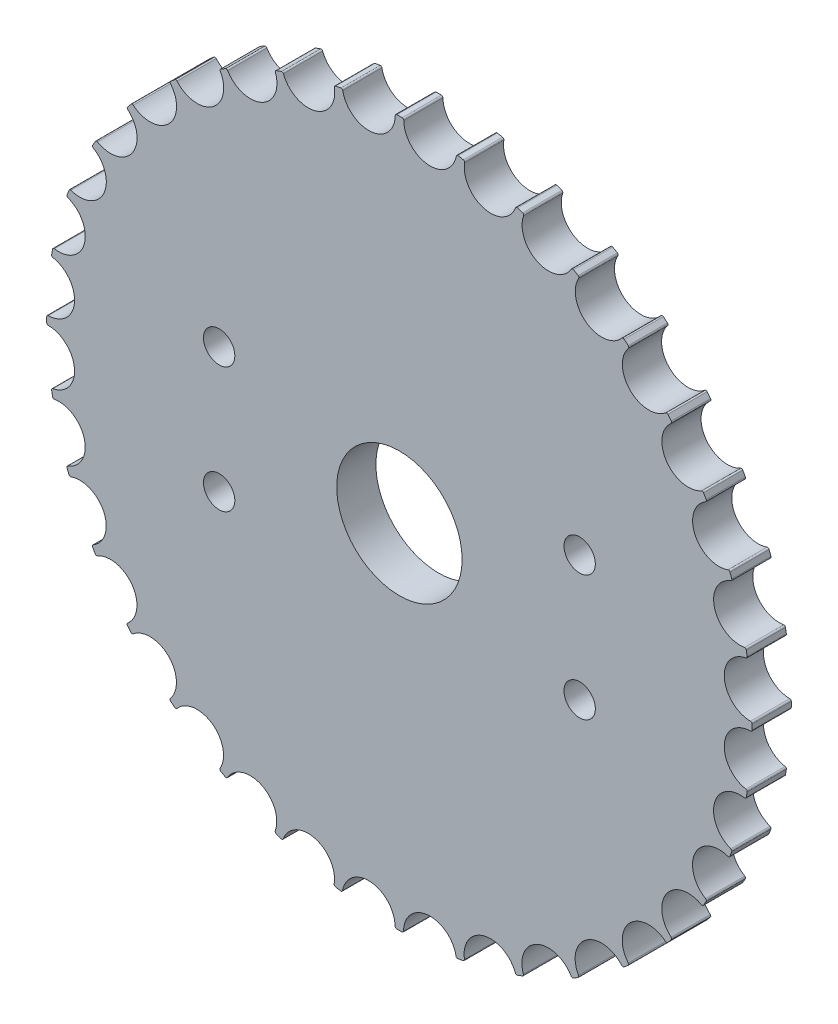
SolidWorks part; units mm, degrees
ref_plane "정면" through (0, 0, 0) normal (0, 0, 1) x (1, 0, 0)
ref_plane "윗면" through (0, 0, 0) normal (0, 1, 0) x (1, 0, 0)
ref_plane "우측면" through (0, 0, 0) normal (1, 0, 0) x (0, 0, -1)
sketch "스케치1" plane through (0, 0, 0) normal (0, 0, 1) x (1, 0, 0)
  circle A0 centre (0, 0) radius 45
extrude "보스-돌출1" add sketch "스케치1" along normal blind 5
sketch "스케치2" plane through (0, 0, 5) normal (0, 0, 1) x (1, 0, 0)
  line L0 (0, 0) -> (0, 53.4651) construction
  line L1 (0, 0) -> (9.1386, 52.0133) construction
  line L2 (0, 0) -> (-9.7027, 52.5525) construction
  circle A0 centre (3.9357, 44.8276) radius 3.38
  circle A2 centre (0, 0) radius 45 construction
  circle A6 centre (11.6601, 43.4631) radius 3.38
  circle A7 centre (19.0303, 40.778) radius 3.38
  circle A8 centre (25.8222, 36.854) radius 3.38
  circle A9 centre (31.8295, 31.8101) radius 3.38
  circle A10 centre (36.8697, 25.7997) radius 3.38
  circle A11 centre (40.7897, 19.0054) radius 3.38
  circle A12 centre (43.4702, 11.6336) radius 3.38
  circle A13 centre (44.83, 3.9083) radius 3.38
  circle A14 centre (44.8276, -3.9357) radius 3.38
  circle A15 centre (43.4631, -11.6601) radius 3.38
  circle A16 centre (40.778, -19.0303) radius 3.38
  circle A17 centre (36.854, -25.8222) radius 3.38
  circle A18 centre (31.8101, -31.8295) radius 3.38
  circle A19 centre (25.7997, -36.8697) radius 3.38
  circle A20 centre (19.0054, -40.7897) radius 3.38
  circle A21 centre (11.6336, -43.4702) radius 3.38
  circle A22 centre (3.9083, -44.83) radius 3.38
  circle A23 centre (-3.9357, -44.8276) radius 3.38
  circle A24 centre (-11.6601, -43.4631) radius 3.38
  circle A25 centre (-19.0303, -40.778) radius 3.38
  circle A26 centre (-25.8222, -36.854) radius 3.38
  circle A27 centre (-31.8295, -31.8101) radius 3.38
  circle A28 centre (-36.8697, -25.7997) radius 3.38
  circle A29 centre (-40.7897, -19.0054) radius 3.38
  circle A30 centre (-43.4702, -11.6336) radius 3.38
  circle A31 centre (-44.83, -3.9083) radius 3.38
  circle A32 centre (-44.8276, 3.9357) radius 3.38
  circle A33 centre (-43.4631, 11.6601) radius 3.38
  circle A34 centre (-40.778, 19.0303) radius 3.38
  circle A35 centre (-36.854, 25.8222) radius 3.38
  circle A36 centre (-31.8101, 31.8295) radius 3.38
  circle A37 centre (-25.7997, 36.8697) radius 3.38
  circle A38 centre (-19.0054, 40.7897) radius 3.38
  circle A39 centre (-11.6336, 43.4702) radius 3.38
  circle A40 centre (-3.9083, 44.83) radius 3.38
  dimension "D1" = 106.9058
  dimension "D2" = 36
extrude "컷-돌출2" cut sketch "스케치2" against normal blind 50
fillet "필렛1" radius 0.2 72 edges at (44.9965, -0.5599, 2.5) (44.4057, -7.2893, 2.5) (44.4101, 7.2621, 2.5) (44.9969, 0.5324, 2.5) (42.4744, 14.8635, 2.5) (44.2208, 8.338, 2.5) (39.2481, 22.0133, 2.5) (42.1011, 15.8901, 2.5) (34.8293, 28.4943, 2.5) (38.7022, 22.9595, 2.5) (29.3521, 34.1094, 2.5) (34.1273, 29.3313, 2.5) (22.9832, 38.6882, 2.5) (28.5156, 34.8118, 2.5) (15.9159, 42.0914, 2.5) (22.0373, 39.2346, 2.5) (44.2157, -8.365, 2.5) (42.4653, -14.8895, 2.5) (42.0914, -15.9159, 2.5) (39.2346, -22.0373, 2.5) (38.6882, -22.9832, 2.5) (34.8118, -28.5156, 2.5) (34.1094, -29.3521, 2.5) (29.3313, -34.1273, 2.5) (28.4943, -34.8293, 2.5) (22.9595, -38.7022, 2.5) (22.0133, -39.2481, 2.5) (15.8901, -42.1011, 2.5) (14.8635, -42.4744, 2.5) (8.338, -44.2208, 2.5) (7.2621, -44.4101, 2.5) (0.5324, -44.9969, 2.5) (-0.5599, -44.9965, 2.5) (-7.2893, -44.4057, 2.5) (-8.365, -44.2157, 2.5) (-14.8895, -42.4653, 2.5) (-15.9159, -42.0914, 2.5) (-22.0373, -39.2346, 2.5) (-22.9832, -38.6882, 2.5) (-28.5156, -34.8118, 2.5) (-29.3521, -34.1094, 2.5) (-34.1273, -29.3313, 2.5) (-34.8293, -28.4943, 2.5) (-38.7022, -22.9595, 2.5) (-39.2481, -22.0133, 2.5) (-42.1011, -15.8901, 2.5) (-42.4744, -14.8635, 2.5) (-44.2208, -8.338, 2.5) (-44.4101, -7.2621, 2.5) (-44.9969, -0.5324, 2.5) (-44.9965, 0.5599, 2.5) (-44.4057, 7.2893, 2.5) (-44.2157, 8.365, 2.5) (-42.4653, 14.8895, 2.5) (-42.0914, 15.9159, 2.5) (-39.2346, 22.0373, 2.5) (-38.6882, 22.9832, 2.5) (-34.8118, 28.5156, 2.5) (-34.1094, 29.3521, 2.5) (-29.3313, 34.1273, 2.5) (-28.4943, 34.8293, 2.5) (-22.9595, 38.7022, 2.5) (-22.0133, 39.2481, 2.5) (-15.8901, 42.1011, 2.5) (-14.8635, 42.4744, 2.5) (-8.338, 44.2208, 2.5) (-7.2621, 44.4101, 2.5) (-0.5324, 44.9969, 2.5) (0.5599, 44.9965, 2.5) (7.2893, 44.4057, 2.5) (8.365, 44.2157, 2.5) (14.8895, 42.4653, 2.5)
sketch "스케치4" plane through (0, 0, 5) normal (0, 0, 1) x (1, 0, 0)
  circle A0 centre (0, 0) radius 8
  dimension "D1" = 16
extrude "컷-돌출3" cut sketch "스케치4" against normal blind 10
sketch "스케치5" plane through (0, 0, 5) normal (0, 0, 1) x (1, 0, 0)
  line L0 (-52.1074, 0) -> (52.2141, 0) construction
  line L1 (-52.1074, -15) -> (52.2141, -15)
  line L2 (-52.1074, 15) -> (52.2141, 15)
  line L3 (0, 53.1222) -> (0, -55.2945) construction
  line L4 (-30, 53.1222) -> (-30, -55.2945)
  line L5 (30, 53.1222) -> (30, -55.2945)
  circle A0 centre (-23, 8) radius 2
  circle A1 centre (23, 8) radius 2
  circle A2 centre (23, -8) radius 2
  circle A3 centre (-23, -8) radius 2
  dimension "D5" = 4
  dimension "D7" = 7
  dimension "D6" = 7
  dimension "D1" = 15
  dimension "D2" = 15
  dimension "D3" = 30
  dimension "D4" = 30
extrude "컷-돌출4" cut sketch "스케치5" against normal blind 10 contours A3 | A0 | A1 | A2
